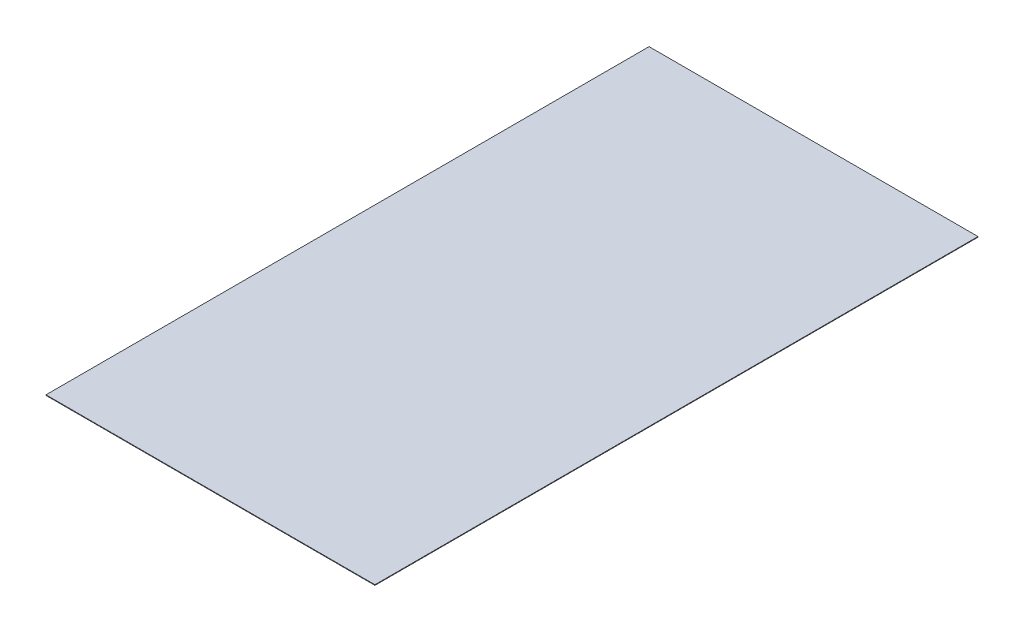
SolidWorks part; units mm, degrees
ref_plane "Front Plane" through (0, 0, 0) normal (0, 0, 1) x (1, 0, 0)
ref_plane "Top Plane" through (0, 0, 0) normal (0, 1, 0) x (1, 0, 0)
ref_plane "Right Plane" through (0, 0, 0) normal (1, 0, 0) x (0, 0, -1)
sketch "Sketch1" plane through (0, 0, 0) normal (0, 1, 0) x (1, 0, 0)
  line L1 (-1828.8, 3352.8) -> (1828.8, 3352.8)
  line L2 (-1828.8, 3352.8) -> (-1828.8, -3352.8)
  line L3 (-1828.8, -3352.8) -> (1828.8, -3352.8)
  line L4 (1828.8, 3352.8) -> (1828.8, -3352.8)
  line L5 (-1828.8, 3352.8) -> (1828.8, -3352.8) construction
  line L6 (-1828.8, -3352.8) -> (1828.8, 3352.8) construction
  point P0 (0, 0)
  dimension "D1" = 3657.6
  dimension "D2" = 6705.6
extrude "Boss-Extrude1" add sketch "Sketch1" along normal blind 6.35
